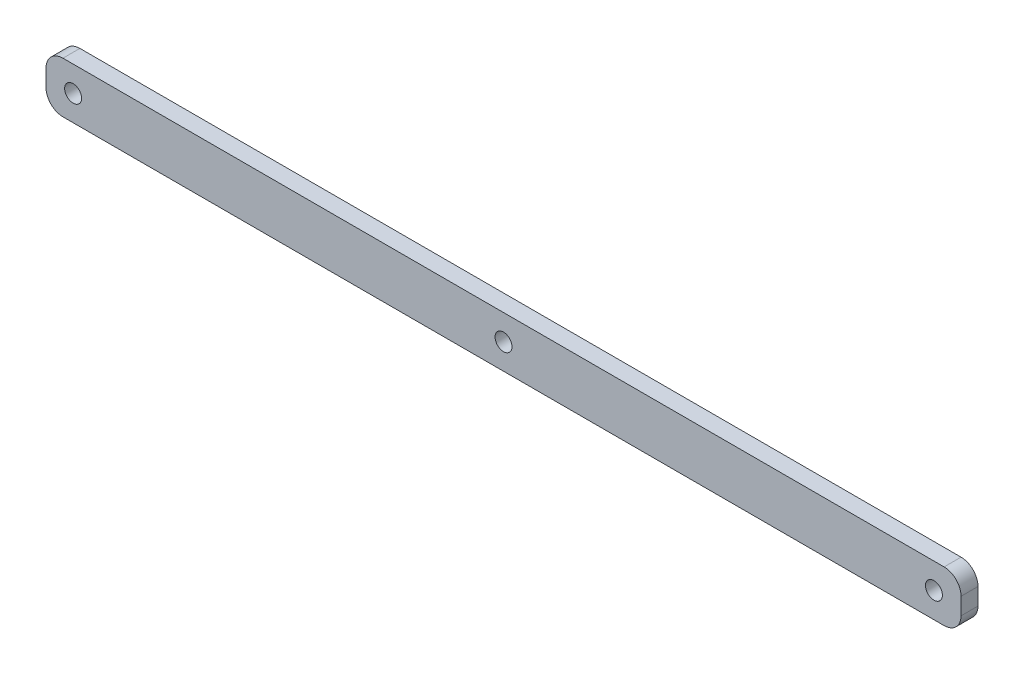
SolidWorks part; units mm, degrees
ref_plane "Front Plane" through (0, 0, 0) normal (0, 0, 1) x (1, 0, 0)
ref_plane "Top Plane" through (0, 0, 0) normal (0, 1, 0) x (1, 0, 0)
ref_plane "Right Plane" through (0, 0, 0) normal (1, 0, 0) x (0, 0, -1)
sketch "Sketch2" plane through (0, 0, 0) normal (0, 0, 1) x (1, 0, 0)
  line L0 (-260, 0) -> (260, 0)
  line L1 (-270, 10) -> (-270, 20)
  line L2 (-260, 30) -> (260, 30)
  line L3 (270, 20) -> (270, 10)
  arc A0 (260, 0) -> (270, 10) centre (260, 10) ccw
  arc A1 (260, 30) -> (270, 20) centre (260, 20) cw
  arc A2 (-260, 0) -> (-270, 10) centre (-260, 10) cw
  arc A3 (-270, 20) -> (-260, 30) centre (-260, 20) cw
  point P7 (270, 0)
  point P12 (-270, 0)
  point P15 (-270, 30)
  dimension "D3" = 10
  dimension "D1" = 540
  dimension "D2" = 30
extrude "Boss-Extrude1" add sketch "Sketch2" along normal blind 10
sketch "Sketch3" plane through (0, 0, 0) normal (0, 0, -1) x (-1, 0, 0)
  line L0 (0, 0) -> (0, 30) construction
  line L1 (-260, 30) -> (260, 30) construction
  line L2 (0, 15) -> (254, 15) construction
  circle A0 centre (254, 15) radius 5
  circle A1 centre (-254, 15) radius 5
  dimension "D1" = 10
  dimension "D3" = 254
  dimension "D5" = 10
  dimension "D2" = 254
extrude "Cut-Extrude1" cut sketch "Sketch3" against normal through all
sketch "Sketch4" plane through (0, 0, 0) normal (0, 0, -1) x (-1, 0, 0)
  line L0 (0, 0) -> (0, 44.6396) construction
  line L1 (260, 0) -> (-260, 0) construction
  circle A0 centre (0, 15) radius 5
  dimension "D1" = 15
  dimension "D2" = 10
extrude "Cut-Extrude2" cut sketch "Sketch4" against normal through all
